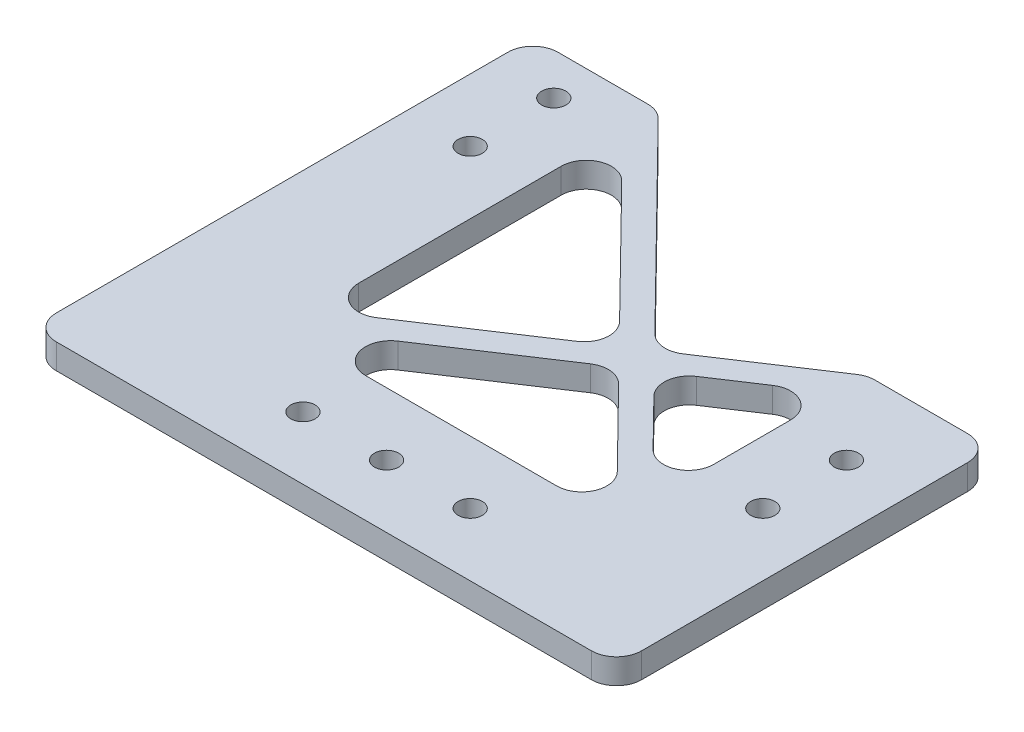
SolidWorks part; units mm, degrees
material "Thornel Mat VMA"
ref_plane "前视基准面" through (0, 0, 0) normal (0, 0, 1) x (1, 0, 0)
ref_plane "上视基准面" through (0, 0, 0) normal (0, 1, 0) x (1, 0, 0)
ref_plane "右视基准面" through (0, 0, 0) normal (1, 0, 0) x (0, 0, -1)
other "Configuration Table"
sketch "草图1" plane through (0, 0, 0) normal (0, 1, 0) x (1, 0, 0)
  line L0 (-20, 52.5) -> (-20, 7.5) construction
  line L1 (-35, -7.5) -> (35, -7.5)
  line L2 (-35, -7.5) -> (-35, 7.5)
  line L3 (-35, 7.5) -> (35, 7.5) construction
  line L4 (35, -7.5) -> (35, 7.5)
  line L5 (-35, -7.5) -> (35, 7.5) construction
  line L6 (-35, 7.5) -> (35, -7.5) construction
  line L7 (-35, -7.5) -> (-20, -7.5)
  line L8 (-35, -7.5) -> (-35, 52.5)
  line L9 (-35, 52.5) -> (-20, 52.5)
  line L10 (-20, -7.5) -> (-20, 52.5) construction
  line L11 (35, -7.5) -> (20, -7.5)
  line L12 (35, -7.5) -> (35, 37.5)
  line L13 (35, 37.5) -> (20, 37.5)
  line L14 (20, -7.5) -> (20, 37.5) construction
  line L15 (-20, 7.5) -> (20, 7.5)
  line L16 (20, 7.5) -> (20, 37.5) construction
  line L17 (-27.5, 80.0831) -> (-27.5, -54.2331) construction
  line L18 (27.5, 41.905) -> (27.5, -46.2561) construction
  line L19 (-50.2964, 0) -> (68.2187, 0) construction
  line L20 (-20, 52.5) -> (20, 11.7809) construction
  line L21 (-20, 48.2191) -> (20, 7.5) construction
  line L22 (20, 37.5) -> (-20, 11.0947) construction
  line L23 (-20, 7.5) -> (20, 33.9053) construction
  line L24 (-20, 52.5) -> (4.6738, 27.3827)
  line L25 (4.6738, 27.3827) -> (20, 37.5)
  line L26 (-20, 48.2191) -> (2.1227, 25.6986)
  line L27 (2.1227, 25.6986) -> (-20, 11.0947)
  line L28 (-20, 11.0947) -> (-20, 48.2191)
  line L29 (-20, 7.5) -> (4.2649, 23.518)
  line L30 (4.2649, 23.518) -> (20, 7.5)
  line L31 (20, 33.9053) -> (6.8159, 25.202)
  line L32 (6.8159, 25.202) -> (20, 11.7809)
  line L33 (20, 11.7809) -> (20, 33.9053)
  circle A0 centre (-27.5, 37.5) radius 1.45
  circle A1 centre (-27.5, 47.5) radius 1.45
  circle A2 centre (27.5, 27.5) radius 1.45
  circle A3 centre (27.5, 17.5) radius 1.45
  circle A4 centre (0, 0) radius 1.45
  circle A5 centre (10, 0) radius 1.45
  circle A6 centre (-10, 0) radius 1.45
  point P0 (0, 0)
  dimension "D5" = 2.9
  dimension "D6" = 30
  dimension "D7" = 10
  dimension "D8" = 5
  dimension "D10" = 10
  dimension "D11" = 10
  dimension "D12" = 10
  dimension "D13" = 10
  dimension "D1" = 70
  dimension "D2" = 15
  dimension "D3" = 15
  dimension "D4" = 15
  dimension "D9" = 10
  dimension "D14" = 3
  dimension "D15" = 3
extrude "凸台-拉伸1" add sketch "草图1" along normal blind 3 contours L16 L15 L0 L9 L8 L2 L1 L4 L12 L13 A6 A5 A4 A3 A2 A1 A0
fillet "圆角1" radius 3 16 edges at (35, 1.5, -37.5) (35, 1.5, 7.5) (-35, 1.5, 7.5) (-35, 1.5, -52.5) (-20, 1.5, -7.5) (20, 1.5, -7.5) (4.2649, 1.5, -23.518) (2.1227, 1.5, -25.6986) (-20, 1.5, -48.2191) (-20, 1.5, -11.0947) (20, 1.5, -37.5) (4.6738, 1.5, -27.3827) (20, 1.5, -33.9053) (6.8159, 1.5, -25.202) (20, 1.5, -11.7809) (-20, 1.5, -52.5)
